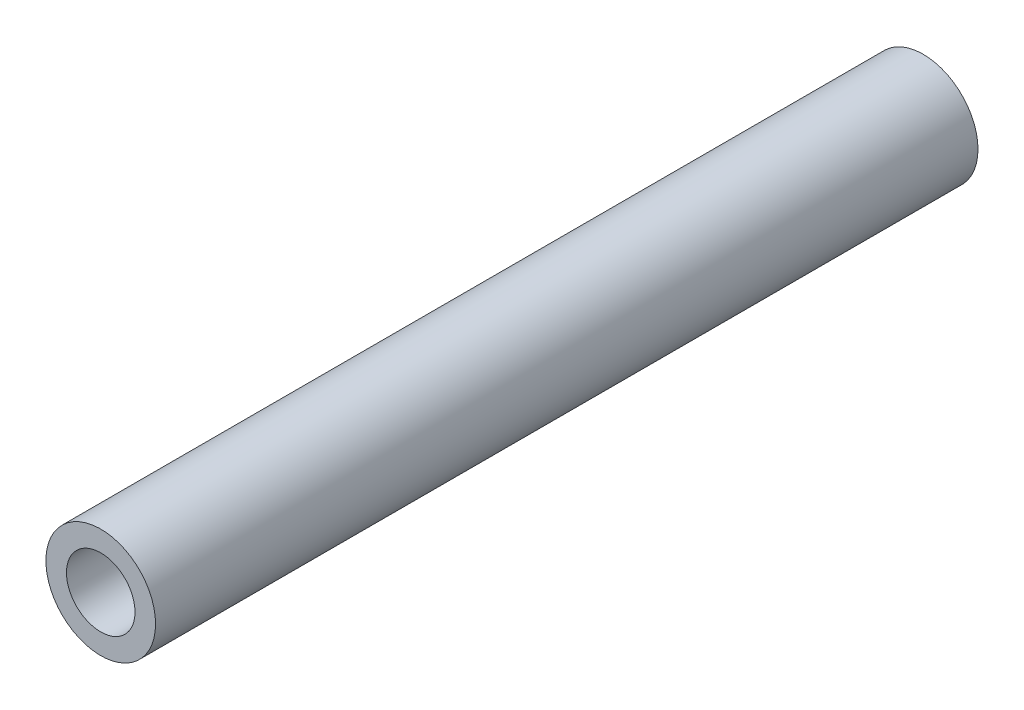
SolidWorks part; units mm, degrees
ref_plane "Plan de face" through (0, 0, 0) normal (0, 0, 1) x (1, 0, 0)
ref_plane "Plan de dessus" through (0, 0, 0) normal (0, 1, 0) x (1, 0, 0)
ref_plane "Plan de droite" through (0, 0, 0) normal (1, 0, 0) x (0, 0, -1)
sketch "Esquisse1" plane through (0, 0, 0) normal (0, 0, 1) x (1, 0, 0)
  circle A0 centre (0, 0) radius 2
  circle A1 centre (0, 0) radius 1.25
  dimension "D1" = 4
  dimension "D2" = 2.5
extrude "Boss.-Extru.1" add sketch "Esquisse1" along normal blind 30
